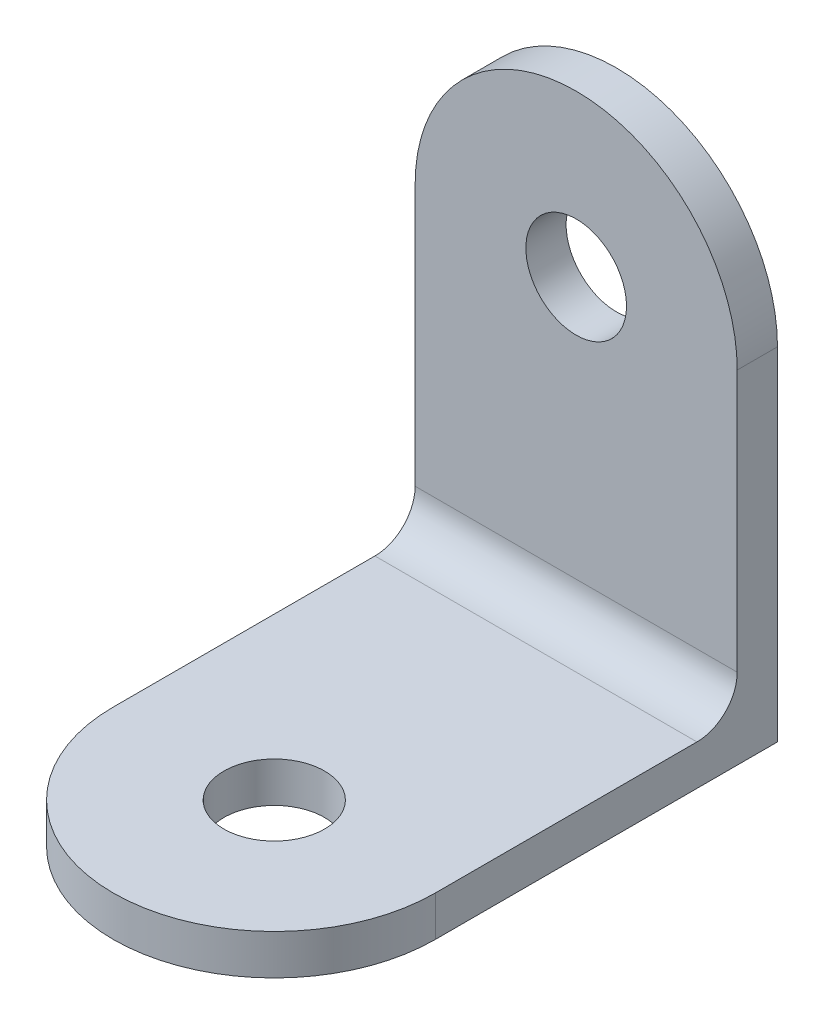
SolidWorks part; units mm, degrees
material "6061 合金"
ref_plane "前视基准面" through (0, 0, 0) normal (0, 0, 1) x (1, 0, 0)
ref_plane "上视基准面" through (0, 0, 0) normal (0, 1, 0) x (1, 0, 0)
ref_plane "右视基准面" through (0, 0, 0) normal (1, 0, 0) x (0, 0, -1)
sketch "草图1" plane through (0, 0, 0) normal (1, 0, 0) x (0, 0, -1)
  line L0 (0, 0) -> (17, 0)
  line L1 (17, 0) -> (17, 17)
  line L2 (17, 17) -> (15, 17)
  line L3 (15, 17) -> (15, 2)
  line L4 (15, 2) -> (0, 2)
  line L5 (0, 2) -> (0, 0)
  dimension "D1" = 17
  dimension "D2" = 17
  dimension "D3" = 2
  dimension "D4" = 2
extrude "凸台-拉伸1" add sketch "草图1" along normal blind 16
sketch "草图2" plane through (0, 0, -15) normal (0, 0, 1) x (1, 0, 0)
  line L0 (0, 17) -> (16, 17)
  arc A0 (0, 17) -> (16, 17) centre (8, 17) cw
  dimension "D1" = 8
extrude "凸台-拉伸2" add sketch "草图2" against normal up to surface (2 mm away) up to face at (8, 8.5, -17)
fillet "圆角1" radius 2 1 edges at (8, 2, -15)
sketch "草图3" plane through (0, 2, 0) normal (0, 1, 0) x (1, 0, 0)
  line L0 (0, 0) -> (16, 0)
  arc A0 (16, 0) -> (0, 0) centre (8, 0) cw
extrude "凸台-拉伸3" add sketch "草图3" against normal up to surface (2 mm away) up to face at (8, 0, -8.5)
sketch "草图4" plane through (0, 0, -15) normal (0, 0, 1) x (1, 0, 0)
  circle A0 centre (8, 17) radius 2.5
  dimension "D1" = 5
extrude "切除-拉伸1" cut sketch "草图4" against normal blind 16
sketch "草图5" plane through (0, 2, 0) normal (0, 1, 0) x (1, 0, 0)
  circle A0 centre (8, 0) radius 2.5
  dimension "D1" = 5
extrude "切除-拉伸2" cut sketch "草图5" against normal blind 16
